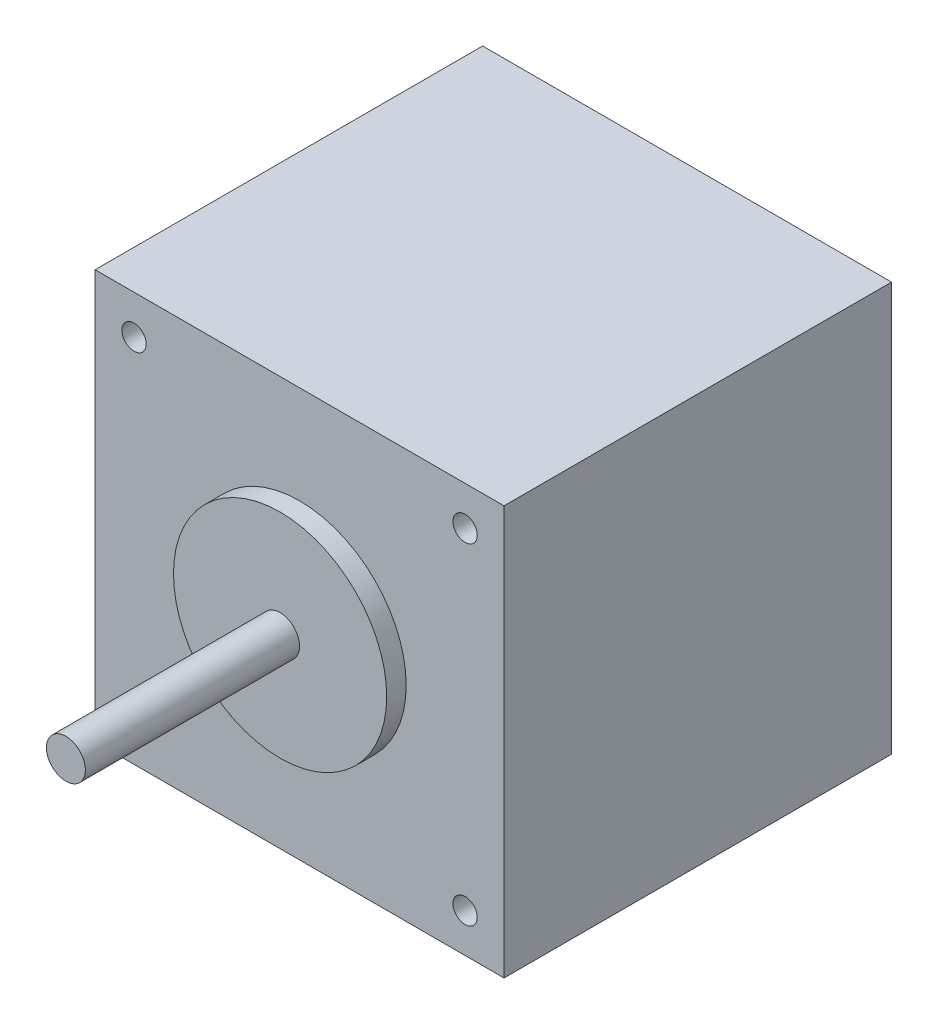
SolidWorks part; units mm, degrees
ref_plane "Front Plane" through (0, 0, 0) normal (0, 0, 1) x (1, 0, 0)
ref_plane "Top Plane" through (0, 0, 0) normal (0, 1, 0) x (1, 0, 0)
ref_plane "Right Plane" through (0, 0, 0) normal (1, 0, 0) x (0, 0, -1)
sketch "Sketch1" plane through (0, 0, 0) normal (0, 0, 1) x (1, 0, 0)
  line L1 (-21, -21) -> (21, -21)
  line L2 (-21, -21) -> (-21, 21)
  line L3 (-21, 21) -> (21, 21)
  line L4 (21, -21) -> (21, 21)
  line L5 (-21, -21) -> (21, 21) construction
  line L6 (-21, 21) -> (21, -21) construction
  point P0 (0, 0)
  dimension "D1" = 42
  dimension "D2" = 42
extrude "Boss-Extrude1" add sketch "Sketch1" along normal blind 39.8
sketch "Sketch2" plane through (0, 0, 39.8) normal (0, 0, 1) x (1, 0, 0)
  circle A0 centre (0, 0) radius 10.95
  dimension "D1" = 21.9
extrude "Boss-Extrude2" add sketch "Sketch2" along normal blind 2
sketch "Sketch3" plane through (0, 0, 39.8) normal (0, 0, 1) x (1, 0, 0)
  line L0 (-21, 21) -> (-21, -21) construction
  line L1 (21, 21) -> (-21, 21) construction
  line L2 (21, -21) -> (21, 21) construction
  line L3 (-21, -21) -> (21, -21) construction
  circle A0 centre (-17, 17) radius 1.25
  circle A1 centre (17, 17) radius 1.25
  circle A2 centre (17, -17) radius 1.25
  circle A3 centre (-17, -17) radius 1.25
  dimension "D9" = 2.5
  dimension "D10" = 2.5
  dimension "D11" = 2.5
  dimension "D12" = 2.5
  dimension "D1" = 4
  dimension "D2" = 4
  dimension "D3" = 4
  dimension "D4" = 4
  dimension "D5" = 4
  dimension "D6" = 4
  dimension "D7" = 4
  dimension "D8" = 4
extrude "Cut-Extrude1" cut sketch "Sketch3" against normal blind 10
sketch "Sketch4" plane through (0, 0, 41.8) normal (0, 0, 1) x (1, 0, 0)
  circle A0 centre (0, 0) radius 2
  dimension "D1" = 4
extrude "Boss-Extrude3" add sketch "Sketch4" along normal blind 22
